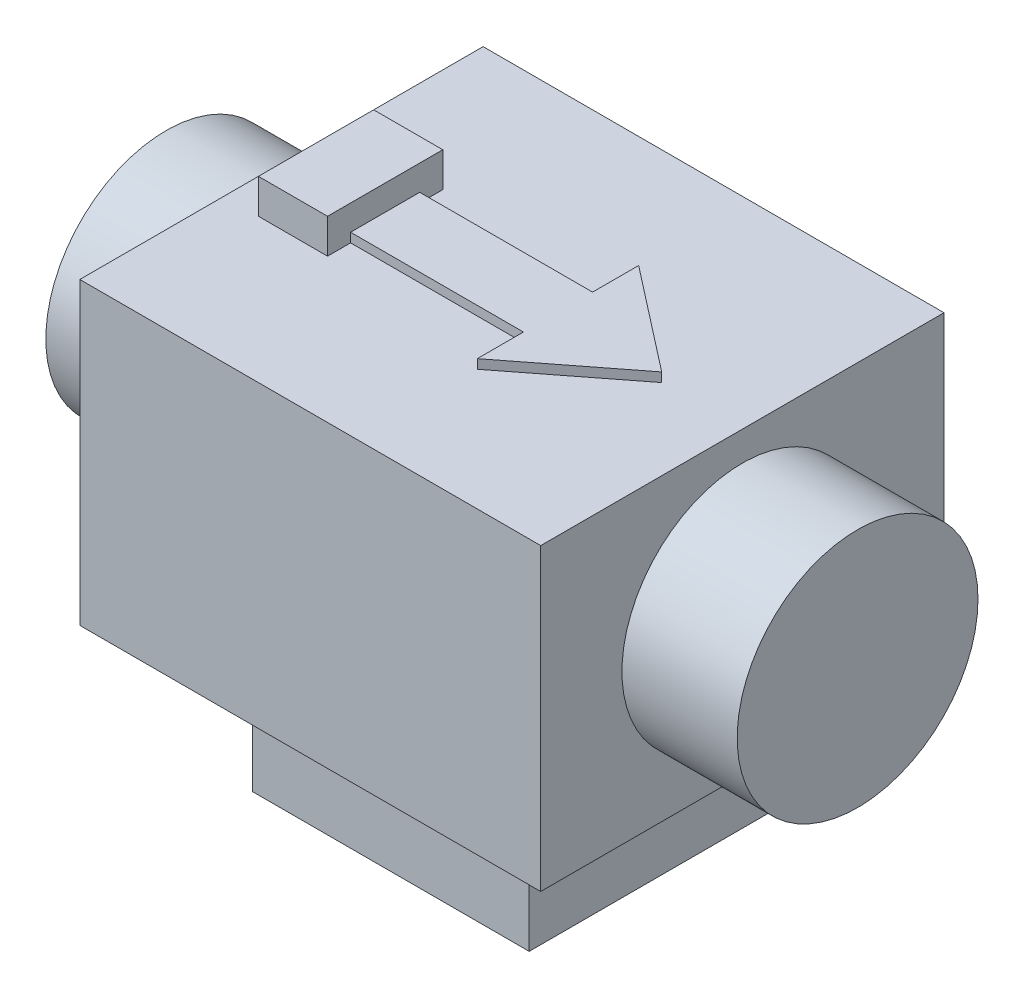
SolidWorks part; units mm, degrees
ref_plane "Front Plane" through (0, 0, 0) normal (0, 0, 1) x (1, 0, 0)
ref_plane "Top Plane" through (0, 0, 0) normal (0, 1, 0) x (1, 0, 0)
ref_plane "Right Plane" through (0, 0, 0) normal (1, 0, 0) x (0, 0, -1)
other "Configuration Table"
sketch "Sketch1" plane through (0, 0, 0) normal (0, 1, 0) x (1, 0, 0)
  line L1 (-20, -17.5) -> (20, -17.5)
  line L2 (-20, -17.5) -> (-20, 17.5)
  line L3 (-20, 17.5) -> (20, 17.5)
  line L4 (20, -17.5) -> (20, 17.5)
  line L5 (-20, -17.5) -> (20, 17.5) construction
  line L6 (-20, 17.5) -> (20, -17.5) construction
extrude "Body" add sketch "Sketch1" along normal blind 26 from offset 12
sketch "Sketch2" plane through (0, 0, 0) normal (1, 0, 0) x (0, 0, -1)
  circle A0 centre (0, 25) radius 10.45
  dimension "D1" = 20.9
extrude "Port_In_G12" add sketch "Sketch2" along normal blind 10 from offset 30
sketch "Sketch3" plane through (0, 0, 0) normal (1, 0, 0) x (0, 0, -1)
  circle A0 centre (0, 25) radius 10.45
  dimension "D1" = 20.9
extrude "Port_Out_G12" add sketch "Sketch3" along normal blind 10 from offset 20
sketch "Sketch4" plane through (0, 0, 0) normal (0, 1, 0) x (1, 0, 0)
  line L1 (-12, -10.5) -> (12, -10.5)
  line L2 (-12, -10.5) -> (-12, 10.5)
  line L3 (-12, 10.5) -> (12, 10.5)
  line L4 (12, -10.5) -> (12, 10.5)
  line L5 (-12, -10.5) -> (12, 10.5) construction
  line L6 (-12, 10.5) -> (12, -10.5) construction
extrude "Feet" add sketch "Sketch4" along normal blind 12
sketch "Sketch5" plane through (0, 0, 0) normal (0, 1, 0) x (1, 0, 0)
  line L0 (-12, 3) -> (4, 3)
  line L1 (4, 3) -> (4, 7)
  line L2 (4, 7) -> (13, 0)
  line L3 (13, 0) -> (4, -7)
  line L4 (4, -7) -> (4, -3)
  line L5 (4, -3) -> (-12, -3)
  line L6 (-12, -3) -> (-12, 3)
extrude "Flow_Arrow" add sketch "Sketch5" along normal blind 0.8 from offset 38
sketch "Sketch6" plane through (0, 0, 0) normal (0, 1, 0) x (1, 0, 0)
  line L1 (-17, -5) -> (-11, -5)
  line L2 (-17, -5) -> (-17, 5)
  line L3 (-17, 5) -> (-11, 5)
  line L4 (-11, -5) -> (-11, 5)
  line L5 (-17, -5) -> (-11, 5) construction
  line L6 (-17, 5) -> (-11, -5) construction
extrude "Wire_Exit" add sketch "Sketch6" along normal blind 3 from offset 38
equation "\"fs_L\"= 60.0   'ASSUMPTION: Flow sensor overall length incl. ports (PDF fallback)"
equation "\"fs_W\"= 35.0   'ASSUMPTION: Flow sensor width (PDF fallback)"
equation "\"fs_H\"= 26.0   'ASSUMPTION: Flow sensor height (PDF fallback)"
equation "\"fs_port_L\"= 10.0   'ASSUMPTION: G1/2 thread length each end (designer choice)"
equation "\"g12_D\"= 20.9   'ASSUMPTION: G1/2 thread major diameter (standard ISO 228)"
equation "\"axis_h\"= 25.0   'ASSUMPTION: Height of the water-line axis above the plate (designer choice)"
equation "\"D1@Body\" = \"fs_H\""
equation "\"D1@Sketch2\" = \"g12_D\""
equation "\"D1@Port_In_G12\" = \"fs_port_L\""
equation "\"D1@Sketch3\" = \"g12_D\""
equation "\"D1@Port_Out_G12\" = \"fs_port_L\""
